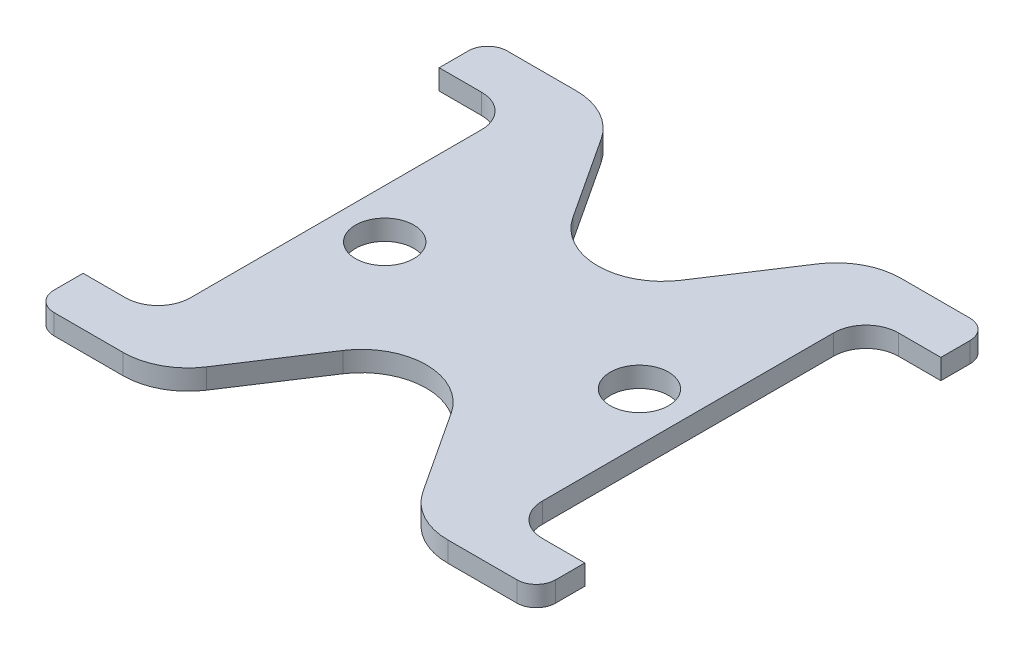
SolidWorks part; units mm, degrees
material "Delrin 2700 NC010, Low Viscosity Acetal Copolymer (SS)"
ref_plane "Front Plane" through (0, 0, 0) normal (0, 0, 1) x (1, 0, 0)
ref_plane "Top Plane" through (0, 0, 0) normal (0, 1, 0) x (1, 0, 0)
ref_plane "Right Plane" through (0, 0, 0) normal (1, 0, 0) x (0, 0, -1)
ref_plane "Plane1" through (0, -32.6579, 0) normal (0, -1, 0) x (1, 0, 0)
sketch "Sketch2" plane through (0, -32.6579, 0) normal (0, -1, 0) x (1, 0, 0)
  line L1 (13.9192, -15.8328) -> (-13.7008, -15.8328)
  line L2 (-19.5758, -12.0228) -> (-13.7008, -12.0228)
  line L3 (13.9192, 19.7272) -> (-13.7008, 19.7272)
  line L4 (-13.7008, -12.0228) -> (-13.7008, 15.9172)
  line L5 (-9.8795, 1.9472) -> (-9.8795, -15.8328) construction
  line L8 (-19.5758, 15.9172) -> (-19.5758, 19.7272)
  line L9 (-19.5758, 19.7272) -> (-13.7008, 19.7272)
  line L10 (-19.5758, 15.9172) -> (-13.7008, 15.9172)
  line L11 (-13.7008, 19.7272) -> (-13.772, 19.8466)
  line L12 (0.1092, -15.8328) -> (0.1092, 41.0144) construction
  line L13 (-19.5758, -12.0228) -> (-19.5758, -15.8328)
  line L14 (-19.5758, -15.8328) -> (-13.7008, -15.8328)
  line L15 (19.7942, 19.7272) -> (13.9192, 19.7272)
  line L16 (-13.7008, 1.9472) -> (30.526, 1.9472) construction
  line L17 (19.7942, -15.8328) -> (13.9192, -15.8328)
  line L18 (19.7942, -12.0228) -> (13.9192, -12.0228)
  line L19 (19.7942, -12.0228) -> (19.7942, -15.8328)
  line L20 (13.9192, -12.0228) -> (13.9192, 15.9172)
  line L21 (19.7942, 15.9172) -> (13.9192, 15.9172)
  line L22 (19.7942, 15.9172) -> (19.7942, 19.7272)
  line L23 (10.1092, -15.8328) -> (10.1092, 1.9472) construction
  line L24 (0.1092, -0.5928) -> (10.1092, -15.8328)
  line L25 (0.1092, -0.5928) -> (-9.8795, -15.8328)
  line L26 (0.1092, 4.4872) -> (10.1092, 19.7272)
  line L27 (0.1092, 4.4872) -> (-9.8795, 19.7272)
  circle A0 centre (10.1092, 1.9472) radius 2.286
  circle A1 centre (10.1092, 1.9472) radius 2.0828 construction
  circle A3 centre (10.1092, 1.9472) radius 2.0828 construction
  circle A4 centre (-9.8795, 1.9472) radius 2.286
  point P35 (0.1092, 19.7272)
  dimension "D8" = 4.572
  dimension "D9" = 4.1656
  dimension "D1" = 3.8214
  dimension "D2" = 3.81
  dimension "D3" = 3.81
  dimension "D4" = 2.54
  dimension "D5" = 27.94
  dimension "D6" = 5.875
  dimension "D7" = 19.9886
extrude "Boss-Extrude1" add sketch "Sketch2" along normal blind 1.5875
fillet "Fillet1" radius 5.08 6 edges at (10.1092, -33.4517, -15.8328) (-9.8795, -33.4517, -15.8328) (10.1092, -33.4517, 19.7272) (-9.8795, -33.4517, 19.7272) (0.1092, -33.4517, 4.4872) (0.1092, -33.4517, -0.5928)
fillet "Fillet2" radius 2.54 4 edges at (13.9192, -33.4517, -12.0228) (13.9192, -33.4517, 15.9172) (-13.7008, -33.4517, 15.9172) (-13.7008, -33.4517, -12.0228)
fillet "Fillet3" radius 1.524 4 edges at (-19.5758, -33.4517, -15.8328) (19.7942, -33.4517, -15.8328) (19.7942, -33.4517, 19.7272) (-19.5758, -33.4517, 19.7272)
